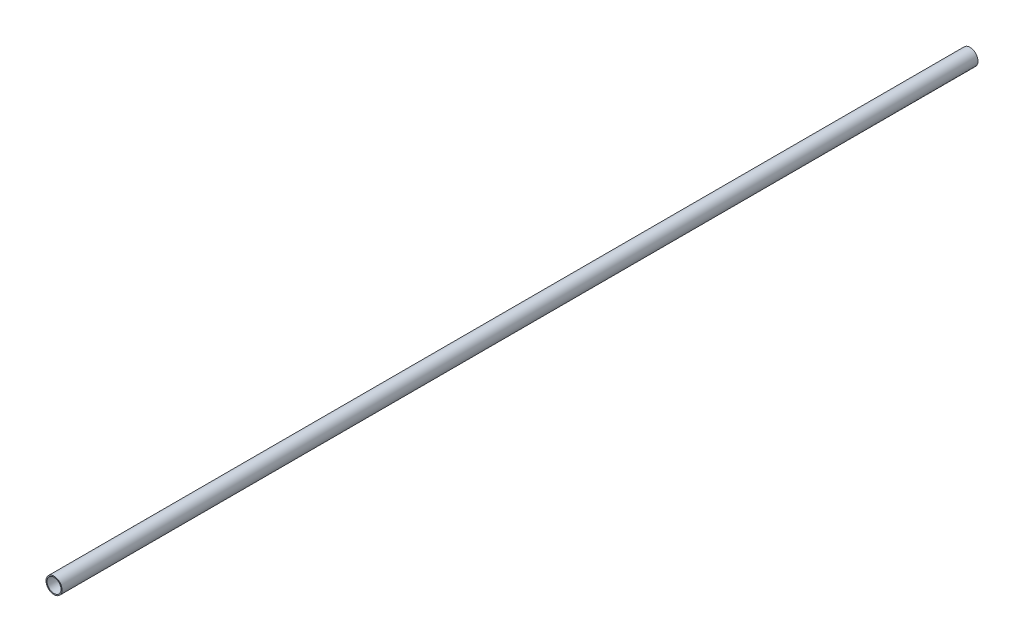
SolidWorks part; units mm, degrees
ref_plane "Plano frontal" through (0, 0, 0) normal (0, 0, 1) x (1, 0, 0)
ref_plane "Plano superior" through (0, 0, 0) normal (0, 1, 0) x (1, 0, 0)
ref_plane "Plano direito" through (0, 0, 0) normal (1, 0, 0) x (0, 0, -1)
sketch "Sketch2" plane through (0, 0, 0) normal (0, 0, 1) x (1, 0, 0)
  circle A0 centre (2449.7201, -5187.0074) radius 24.125
  circle A1 centre (2449.7201, -5187.0074) radius 21.075
  dimension "D1" = 3.05
extrude "Boss-Extrude1" add sketch "Sketch2" along normal blind 2750
